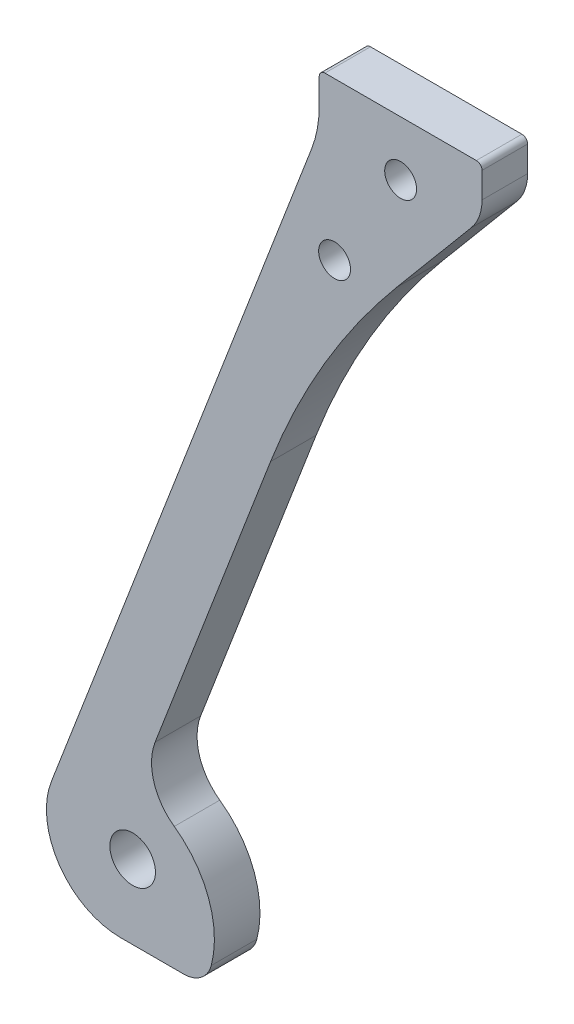
SolidWorks part; units mm, degrees
material "Hexcel AS4C (3000 丝)"
ref_plane "前视基准面" through (0, 0, 0) normal (0, 0, 1) x (1, 0, 0)
ref_plane "上视基准面" through (0, 0, 0) normal (0, 1, 0) x (1, 0, 0)
ref_plane "右视基准面" through (0, 0, 0) normal (1, 0, 0) x (0, 0, -1)
sketch "草图1" plane through (0, 0, 0) normal (0, 0, 1) x (1, 0, 0)
  line L0 (-88.3739, 5) -> (-88.3739, 0) construction
  line L1 (-95.3739, 5) -> (-88.3739, 5) construction
  line L2 (-95.3739, 5) -> (-95.3739, 0) construction
  line L3 (-95.3739, 0) -> (-88.3739, 0) construction
  line L4 (-88.3739, 5) -> (-88.3739, 0) construction
  line L5 (-95.3739, 5) -> (-88.3739, 0) construction
  line L6 (-95.3739, 0) -> (-88.3739, 5) construction
  line L7 (-95.3739, 0.5) -> (-95.3739, 4.5) construction
  line L8 (-88.3739, 5) -> (-27.9117, 5) construction
  line L9 (-27.9117, 0) -> (-88.3739, 0) construction
  line L10 (-95.4739, 5.1) -> (-95.4739, -0.1) construction
  line L11 (-95.4739, -0.1) -> (-88.2739, -0.1) construction
  line L12 (-88.2739, 5.1) -> (-88.2739, -0.1) construction
  line L13 (-95.4739, 5.1) -> (-88.2739, 5.1) construction
  line L14 (-88.7638, 5.1) -> (-94.984, 5.1)
  line L15 (-95.4739, 4.6101) -> (-95.4739, 0.3899)
  line L16 (-94.984, -0.1) -> (-88.7638, -0.1)
  line L17 (-88.2739, 4.6101) -> (-88.2739, 0.3899)
  line L18 (-97.8739, 10.8) -> (-85.8739, 10.8)
  line L19 (-99.684, -6.6313) -> (-122.539, -66.1706)
  line L20 (-83.0739, 8) -> (-100.6739, 8) construction
  line L21 (-91.8739, 8) -> (-91.8739, 2.5) construction
  line L23 (-83.0739, 8) -> (-83.0739, -6.3) construction
  line L24 (-85.6639, -5.6188) -> (-99.3383, -21.9154)
  line L25 (-100.6739, 8) -> (-100.6739, -5) construction
  line L26 (-116.4707, -75) -> (-110.914, -75)
  line L27 (-99.3383, -21.9154) -> (-113.4297, -58.6246)
  line L29 (-108.4959, -73.1348) -> (-110.914, -72.5) construction
  line L30 (-83.4888, 6.5333) -> (-84.4317, 5)
  line L32 (-406.2504, 85.2028) -> (42.4163, 85.2028) construction
  line L33 (-84.728, 3.9523) -> (-84.728, -3.0477)
  line L35 (-99.0198, 3.9523) -> (-99.0198, -3.0477)
  line L36 (-100.259, 6.5333) -> (-99.3161, 5)
  arc A0 (-88.4139, 5.2429) -> (-88.131, 4.96) centre (-88.2739, 5.1) cw
  arc A1 (-88.4139, -0.2429) -> (-88.131, 0.04) centre (-88.2739, -0.1) ccw
  arc A2 (-95.3339, 5.2429) -> (-95.6168, 4.96) centre (-95.4739, 5.1) ccw
  arc A3 (-95.6168, 0.04) -> (-95.3339, -0.2429) centre (-95.4739, -0.1) ccw
  arc A4 (-95.6168, 4.96) -> (-95.4739, 4.6101) centre (-95.9739, 4.6101) cw
  arc A5 (-95.3339, 5.2429) -> (-94.984, 5.1) centre (-94.984, 5.6) ccw
  arc A6 (-95.6168, 0.04) -> (-95.4739, 0.3899) centre (-95.9739, 0.3899) ccw
  arc A7 (-88.131, 0.04) -> (-88.2739, 0.3899) centre (-87.7739, 0.3899) cw
  arc A8 (-88.4139, -0.2429) -> (-88.7638, -0.1) centre (-88.7638, -0.6) ccw
  arc A9 (-88.131, 4.96) -> (-88.2739, 4.6101) centre (-87.7739, 4.6101) ccw
  arc A10 (-88.4139, 5.2429) -> (-88.7638, 5.1) centre (-88.7638, 5.6) cw
  arc A11 (-95.3339, -0.2429) -> (-94.984, -0.1) centre (-94.984, -0.6) cw
  arc A12 (-97.8739, 10.8) -> (-100.6739, 8) centre (-97.8739, 8) ccw
  arc A13 (-85.8739, 10.8) -> (-83.0739, 8) centre (-85.8739, 8) cw
  circle A14 centre (-85.8739, 8) radius 1.4
  circle A15 centre (-97.8739, 8) radius 1.4
  arc A17 (-110.914, -75) -> (-108.4959, -73.1348) centre (-110.914, -72.5) ccw
  circle A19 centre (-97.6739, -14.1) radius 1.4
  arc A21 (-122.539, -66.1706) -> (-116.4707, -75) centre (-116.4707, -68.5) ccw
  circle A22 centre (-91.8739, -5.1) radius 1.4
  arc A24 (-113.4297, -58.6246) -> (-111.7471, -64.1882) centre (-109.0055, -60.3229) ccw
  circle A25 centre (-115.3995, -68.5) radius 2
  arc A26 (-83.0739, 8) -> (-83.4888, 6.5333) centre (-85.8739, 8) cw
  arc A27 (-84.4317, 5) -> (-84.728, 3.9523) centre (-82.728, 3.9523) ccw
  arc A28 (-99.3161, 5) -> (-99.0198, 3.9523) centre (-101.0198, 3.9523) cw
  arc A29 (-100.6739, 8) -> (-100.259, 6.5333) centre (-97.8739, 8) ccw
  arc A30 (-84.728, -3.0477) -> (-85.6639, -5.6188) centre (-88.728, -3.0477) cw
  arc A31 (-99.0198, -3.0477) -> (-99.684, -6.6313) centre (-109.0198, -3.0477) cw
  arc A32 (-111.7471, -64.1882) -> (-108.4959, -73.1348) centre (-116.5864, -71.0109) cw
  point P0 (-91.8739, 2.5)
  point P30 (-95.4739, 4.9)
  point P33 (-95.2739, 5.1)
  point P36 (-95.4739, 0.1)
  point P39 (-88.2739, 0.1)
  point P42 (-88.4739, -0.1)
  point P45 (-88.2739, 4.9)
  point P48 (-88.4739, 5.1)
  point P51 (-95.2739, -0.1)
  dimension "D2" = 0.2
  dimension "D3" = 0.5
  dimension "D4" = 0.5
  dimension "D6" = 2.8
  dimension "D7" = 2.8
  dimension "D9" = 4
  dimension "D11" = 10
  dimension "D13" = 13
  dimension "D17" = 5.8
  dimension "D18" = 6.5
  dimension "D24" = 2.5
  dimension "D26" = 4
  dimension "D30" = 2
  dimension "D5" = 12
  dimension "D8" = 6.3
  dimension "D10" = 40
  dimension "D12" = 159
  dimension "D14" = 14
  dimension "D15" = 3
  dimension "D19" = 5
  dimension "D20" = 75
  dimension "D27" = 6.5
  dimension "D28" = 7.5
  dimension "D29" = 3
  dimension "D31" = 1.8
  dimension "D32" = 7
  dimension "D1" = 0.1
extrude "凸台-拉伸1" add sketch "草图1" along normal blind 4
fillet "圆角1" radius 66 1 edges at (-99.3383, -21.9154, 2)
sketch "草图2" plane through (0, 0, 4) normal (0, 0, 1) x (1, 0, 0)
  line L0 (-85.8739, 10.8) -> (-97.8739, 10.8) construction
  line L1 (-100.6739, 10.8) -> (-83.0739, 10.8)
  line L2 (-100.6739, 10.8) -> (-100.6739, -0.3)
  line L3 (-100.6739, -0.3) -> (-83.0739, -0.3)
  line L4 (-83.0739, 10.8) -> (-83.0739, -0.3)
  line L5 (-100.6739, 10.8) -> (-83.0739, -0.3) construction
  line L6 (-100.6739, -0.3) -> (-83.0739, 10.8) construction
  arc A0 (-88.4139, -0.2429) -> (-88.131, 0.04) centre (-88.2739, -0.1) ccw construction
  arc A1 (-83.4888, 6.5333) -> (-85.8739, 10.8) centre (-85.8739, 8) ccw construction
  arc A2 (-97.8739, 10.8) -> (-100.259, 6.5333) centre (-97.8739, 8) ccw construction
  point P0 (-91.8739, 5.25)
extrude "切除-拉伸1" cut sketch "草图2" against normal through all both and the other way through all
fillet "圆角3" radius 0.5 2 edges at (-84.728, -0.3, 2) (-99.0198, -0.3, 2)
